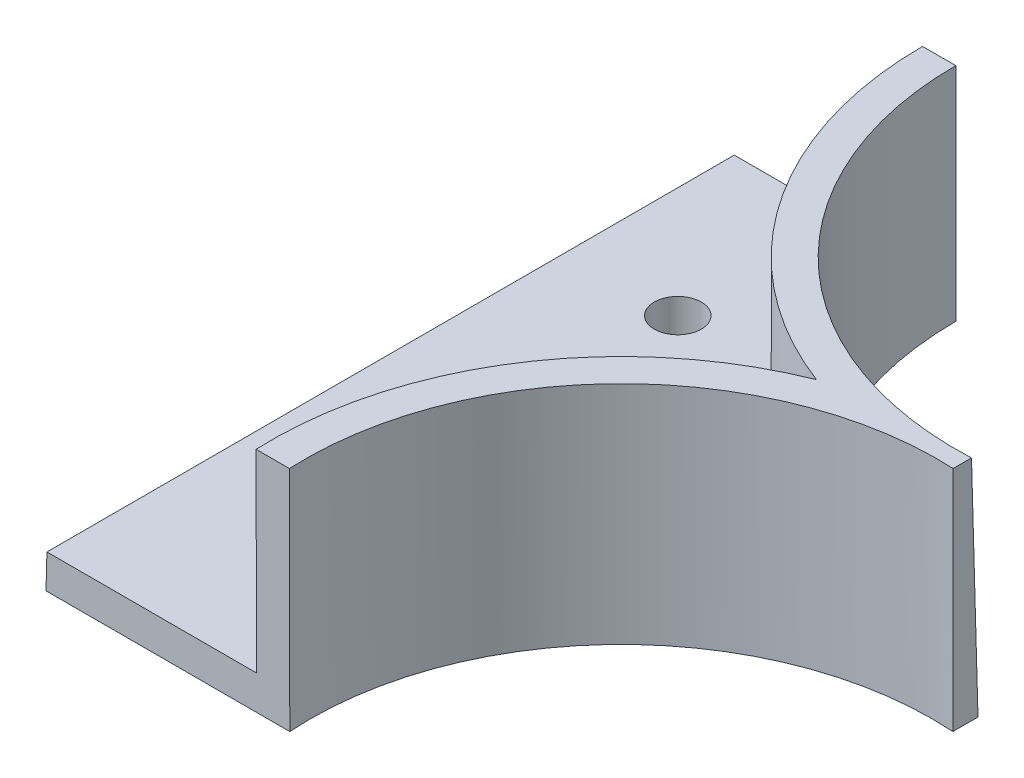
SolidWorks part; units mm, degrees
ref_plane "前基準面" through (0, 0, 0) normal (0, 0, 1) x (1, 0, 0)
ref_plane "上基準面" through (0, 0, 0) normal (0, 1, 0) x (1, 0, 0)
ref_plane "右基準面" through (0, 0, 0) normal (1, 0, 0) x (0, 0, -1)
sketch "草圖1" plane through (0, 0, 0) normal (0, 1, 0) x (1, 0, 0)
  line L6 (0, -55) -> (0, 55) construction
  line L7 (0, 30.1) -> (50, 30.1)
  line L8 (0, 30.1) -> (0, 0)
  line L9 (0, 0) -> (50, 0)
  line L10 (50, 30.1) -> (50, 0)
  line L11 (-55, 0) -> (55, 0) construction
  dimension "D1" = 50
  dimension "D2" = 30.1
extrude "填料-伸長1" add sketch "草圖1" along normal blind 70
sketch "草圖3" plane through (0, 70, 0) normal (0, 1, 0) x (1, 0, 0)
  line L5 (50, 0) -> (50, 30.1) construction
  line L6 (50, 30.1) -> (0, 30.1) construction
  line L7 (20, 30.1) -> (50, 30.1)
  line L8 (50, 30.1) -> (50, 0.1)
  arc A1 (50, 0.1) -> (20, 30.1) centre (50, 30.1) cw
  dimension "D1" = 30
extrude "除料-伸長2" cut sketch "草圖3" against normal blind 70
mirror "鏡射1" about plane through (0, 0, 0) normal (0, 0, 1) of "填料-伸長1", "除料-伸長2"
draft "拔模4" type of draft neutral plane draft angle 1.591 faces to draft 3 face at (50, 35, 0) face at (10, 35, 30.1) face at (31.8934, 35, 11.9934) neutral plane through (0, 70, 0) neutral plane normal (0, 1, 0) parameters "D1"=1.591
sketch "草圖4" plane through (0, 0, 0) normal (-1, 0, 0) x (0, 0, 1)
  line L0 (30.1, 70) -> (32.0443, 0) construction
  line L1 (-30.1, 70) -> (31.4888, 70)
  line L2 (-30.1, 70) -> (-30.1, 20)
  line L3 (-30.1, 20) -> (31.4888, 20)
  line L4 (31.4888, 70) -> (31.4888, 20)
  dimension "D1" = 50
extrude "除料-伸長3" cut sketch "草圖4" against normal through all
shell "薄殼2" thickness 3
sketch "草圖5" plane through (0, 3, 0) normal (0, 1, 0) x (1, 0, 0)
  line L0 (0, -33.11) -> (0, 33.11) construction
  line L1 (-27.5, 0) -> (27.5, 0) construction
  circle A0 centre (10, 15) radius 2.125
  circle A1 centre (10, -15) radius 2.125
  dimension "D1" = 4.25
  dimension "D2" = 10
  dimension "D3" = 15
extrude "除料-伸長4" cut sketch "草圖5" against normal through all
